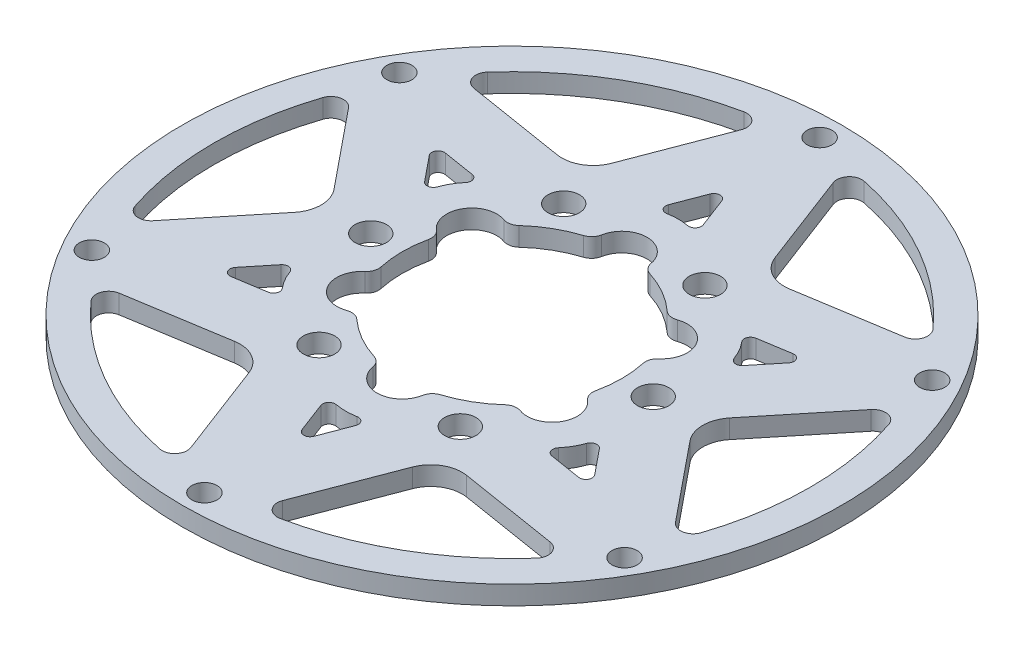
SolidWorks part; units mm, degrees
material "Thornel Mat VMA"
ref_plane "前视基准面" through (0, 0, 0) normal (0, 0, 1) x (1, 0, 0)
ref_plane "上视基准面" through (0, 0, 0) normal (0, 1, 0) x (1, 0, 0)
ref_plane "右视基准面" through (0, 0, 0) normal (1, 0, 0) x (0, 0, -1)
sketch "草图1" plane through (0, 0, 0) normal (0, 1, 0) x (1, 0, 0)
  circle A0 centre (0, 0) radius 52.5
  circle A1 centre (0, 0) radius 49 construction
  circle A2 centre (0, 0) radius 22.5 construction
  circle A3 centre (0, 49) radius 2
  circle A4 centre (-11.25, 19.4856) radius 2.5
  circle A5 centre (42.4352, 24.5) radius 2
  circle A6 centre (11.25, 19.4856) radius 2.5
  circle A7 centre (42.4352, -24.5) radius 2
  circle A8 centre (22.5, 0) radius 2.5
  circle A9 centre (0, -49) radius 2
  circle A10 centre (11.25, -19.4856) radius 2.5
  circle A11 centre (-42.4352, -24.5) radius 2
  circle A12 centre (-11.25, -19.4856) radius 2.5
  circle A13 centre (-42.4352, 24.5) radius 2
  circle A14 centre (-22.5, 0) radius 2.5
  arc A15 (11.797, 12.926) -> (5.2957, 16.6795) centre (0, 0) ccw
  arc A16 (3.934, 18.2238) -> (-3.934, 18.2238) centre (0, 17.5) ccw
  arc A17 (3.934, 18.2238) -> (5.2957, 16.6795) centre (5.901, 18.5857) ccw
  arc A18 (-3.934, 18.2238) -> (-5.2957, 16.6795) centre (-5.901, 18.5857) cw
  arc A19 (17.7493, 5.705) -> (13.8153, 12.5188) centre (15.1554, 8.75) ccw
  arc A20 (13.8153, 12.5188) -> (11.797, 12.926) centre (13.1452, 14.4032) cw
  arc A21 (17.7493, 5.705) -> (17.0927, 3.7535) centre (19.0462, 4.1825) ccw
  arc A22 (17.0927, -3.7535) -> (17.0927, 3.7535) centre (0, 0) ccw
  arc A23 (13.8153, -12.5188) -> (17.7493, -5.705) centre (15.1554, -8.75) ccw
  arc A24 (17.7493, -5.705) -> (17.0927, -3.7535) centre (19.0462, -4.1825) cw
  arc A25 (13.8153, -12.5188) -> (11.797, -12.926) centre (13.1452, -14.4032) ccw
  arc A26 (5.2957, -16.6795) -> (11.797, -12.926) centre (0, 0) ccw
  arc A27 (-3.934, -18.2238) -> (3.934, -18.2238) centre (0, -17.5) ccw
  arc A28 (3.934, -18.2238) -> (5.2957, -16.6795) centre (5.901, -18.5857) cw
  arc A29 (-3.934, -18.2238) -> (-5.2957, -16.6795) centre (-5.901, -18.5857) ccw
  arc A30 (-11.797, -12.926) -> (-5.2957, -16.6795) centre (0, 0) ccw
  arc A31 (-17.7493, -5.705) -> (-13.8153, -12.5188) centre (-15.1554, -8.75) ccw
  arc A32 (-13.8153, -12.5188) -> (-11.797, -12.926) centre (-13.1452, -14.4032) cw
  arc A33 (-17.7493, -5.705) -> (-17.0927, -3.7535) centre (-19.0462, -4.1825) ccw
  arc A34 (-17.0927, 3.7535) -> (-17.0927, -3.7535) centre (0, 0) ccw
  arc A35 (-13.8153, 12.5188) -> (-17.7493, 5.705) centre (-15.1554, 8.75) ccw
  arc A36 (-17.7493, 5.705) -> (-17.0927, 3.7535) centre (-19.0462, 4.1825) cw
  arc A37 (-13.8153, 12.5188) -> (-11.797, 12.926) centre (-13.1452, 14.4032) ccw
  arc A38 (-5.2957, 16.6795) -> (-11.797, 12.926) centre (0, 0) ccw
  point P38 (0, 0)
  point P39 (0, 0)
  point P79 (11.25, 14.189)
  point P80 (11.797, 12.926)
  point P81 (11.6293, 13.0771)
  dimension "D1" = 105
  dimension "D2" = 45
  dimension "D3" = 3.5
  dimension "D4" = 4
  dimension "D5" = 5
  dimension "D7" = 35
  dimension "D8" = 4
  dimension "D9" = 2
  dimension "D6" = 6
extrude "凸台-拉伸1" add sketch "草图1" along normal blind 3
sketch "草图2" plane through (0, 3, 0) normal (0, 1, 0) x (1, 0, 0)
  line L0 (0, 49) -> (-11.25, 19.4856) construction
  line L1 (-11.25, 19.4856) -> (-42.4352, 24.5) construction
  line L2 (0, 49) -> (11.25, 19.4856) construction
  line L3 (-6.0712, 47.1104) -> (-14.473, 25.068)
  line L4 (-14.473, 25.068) -> (-37.7632, 28.813)
  line L5 (0, 34.9619) -> (3.4946, 25.7939)
  line L6 (0, 34.9619) -> (-3.4946, 25.7939)
  line L7 (-4.6721, 50.7809) -> (-14.473, 25.068) construction
  line L8 (-14.473, 25.068) -> (-41.6415, 29.4366) construction
  line L9 (0, 34.9619) -> (-6.5779, 17.7047) construction
  line L10 (0, 34.9619) -> (6.5779, 17.7047) construction
  line L11 (14.473, 25.068) -> (6.0712, 47.1104)
  line L12 (37.7632, 28.813) -> (14.473, 25.068)
  line L13 (30.2779, 17.4809) -> (20.5909, 15.9233)
  line L14 (30.2779, 17.4809) -> (24.0854, 9.8705)
  line L15 (28.9461, 0) -> (43.8344, 18.2974)
  line L16 (43.8344, -18.2974) -> (28.9461, 0)
  line L17 (30.2779, -17.4809) -> (24.0854, -9.8705)
  line L18 (30.2779, -17.4809) -> (20.5909, -15.9233)
  line L19 (14.473, -25.068) -> (37.7632, -28.813)
  line L20 (6.0712, -47.1104) -> (14.473, -25.068)
  line L21 (0, -34.9619) -> (3.4946, -25.7939)
  line L22 (0, -34.9619) -> (-3.4946, -25.7939)
  line L23 (-14.473, -25.068) -> (-6.0712, -47.1104)
  line L24 (-37.7632, -28.813) -> (-14.473, -25.068)
  line L25 (-30.2779, -17.4809) -> (-20.5909, -15.9233)
  line L26 (-30.2779, -17.4809) -> (-24.0854, -9.8705)
  line L27 (-28.9461, 0) -> (-43.8344, -18.2974)
  line L28 (-43.8344, 18.2974) -> (-28.9461, 0)
  line L29 (-30.2779, 17.4809) -> (-24.0854, 9.8705)
  line L30 (-30.2779, 17.4809) -> (-20.5909, 15.9233)
  arc A1 (-6.0712, 47.1104) -> (-37.7632, 28.813) centre (0, 0) ccw
  arc A3 (3.4946, 25.7939) -> (-3.4946, 25.7939) centre (0, 17.5) ccw
  arc A4 (3.934, 18.2238) -> (-3.934, 18.2238) centre (0, 17.5) ccw construction
  arc A5 (37.7632, 28.813) -> (6.0712, 47.1104) centre (0, 0) ccw
  arc A6 (24.0854, 9.8705) -> (20.5909, 15.9233) centre (15.1554, 8.75) ccw
  arc A7 (43.8344, -18.2974) -> (43.8344, 18.2974) centre (0, 0) ccw
  arc A8 (20.5909, -15.9233) -> (24.0854, -9.8705) centre (15.1554, -8.75) ccw
  arc A9 (6.0712, -47.1104) -> (37.7632, -28.813) centre (0, 0) ccw
  arc A10 (-3.4946, -25.7939) -> (3.4946, -25.7939) centre (0, -17.5) ccw
  arc A11 (-37.7632, -28.813) -> (-6.0712, -47.1104) centre (0, 0) ccw
  arc A12 (-24.0854, -9.8705) -> (-20.5909, -15.9233) centre (-15.1554, -8.75) ccw
  arc A13 (-43.8344, 18.2974) -> (-43.8344, -18.2974) centre (0, 0) ccw
  arc A14 (-20.5909, 15.9233) -> (-24.0854, 9.8705) centre (-15.1554, 8.75) ccw
  circle A15 centre (0, 0) radius 52.5 construction
  point P17 (0, 0)
  dimension "D3" = 5
  dimension "D5" = 5
  dimension "D1" = 5
  dimension "D2" = 5
  dimension "D4" = 6
extrude "切除-拉伸1" cut sketch "草图2" against normal through all
fillet "圆角1" radius 5 6 edges at (-28.9461, 1.5, 0) (-14.473, 1.5, 25.068) (14.473, 1.5, 25.068) (28.9461, 1.5, 0) (14.473, 1.5, -25.068) (-14.473, 1.5, -25.068)
fillet "圆角2" radius 1 18 edges at (-20.5909, 1.5, 15.9233) (-30.2779, 1.5, 17.4809) (-24.0854, 1.5, 9.8705) (-24.0854, 1.5, -9.8705) (-30.2779, 1.5, -17.4809) (-20.5909, 1.5, -15.9233) (3.4946, 1.5, -25.7939) (-3.4946, 1.5, -25.7939) (20.5909, 1.5, -15.9233) (30.2779, 1.5, -17.4809) (24.0854, 1.5, -9.8705) (24.0854, 1.5, 9.8705) (30.2779, 1.5, 17.4809) (20.5909, 1.5, 15.9233) (3.4946, 1.5, 25.7939) (0, 1.5, 34.9619) (-3.4946, 1.5, 25.7939) (0, 1.5, -34.9619)
fillet "圆角3" radius 2 12 edges at (-37.7632, 1.5, -28.813) (-43.8344, 1.5, 18.2974) (-43.8344, 1.5, -18.2974) (6.0712, 1.5, -47.1104) (37.7632, 1.5, -28.813) (43.8344, 1.5, -18.2974) (43.8344, 1.5, 18.2974) (37.7632, 1.5, 28.813) (6.0712, 1.5, 47.1104) (-6.0712, 1.5, 47.1104) (-37.7632, 1.5, 28.813) (-6.0712, 1.5, -47.1104)
